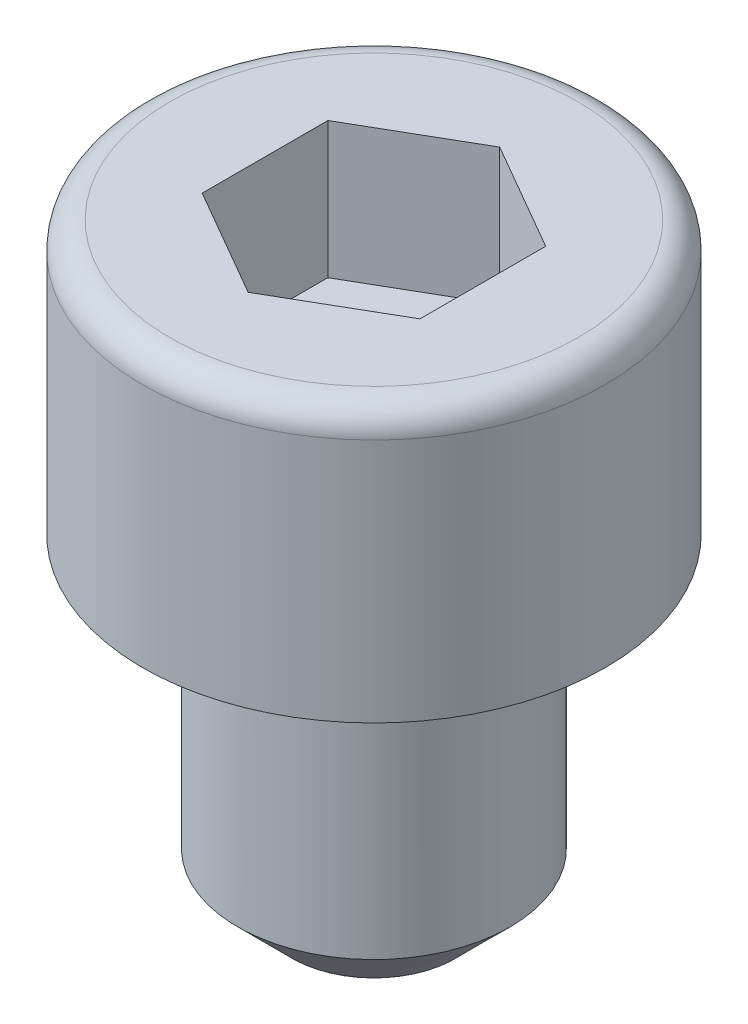
SolidWorks part; units mm, degrees
material "1.4301 (X5CrNi18-10)"
ref_plane "Front Plane" through (0, 0, 0) normal (0, 0, 1) x (1, 0, 0)
ref_plane "Top Plane" through (0, 0, 0) normal (0, 1, 0) x (1, 0, 0)
ref_plane "Right Plane" through (0, 0, 0) normal (1, 0, 0) x (0, 0, -1)
sketch "Sketch1" plane through (0, 0, 0) normal (0, 0, 1) x (1, 0, 0)
  line L0 (0, -1000) -> (0, 49000) construction
  line L1 (0, 0) -> (0, 11)
  line L2 (0, 11) -> (-4.25, 11)
  line L3 (-4.25, 11) -> (-4.25, 6)
  line L4 (-4.25, 6) -> (-2.5, 6)
  line L5 (-2.5, 6) -> (-2.5, 0)
  line L6 (-2.5, 0) -> (0, 0)
  dimension "Imenski premer" = 5
  dimension "Dolzina stebla" = 6
  dimension "Visina glave" = 5
  dimension "Premer glave" = 8.5
revolve "Revolve1" add sketch "Sketch1" angle 360 about L0
sketch "Sketch2" plane through (0, 11, 0) normal (0, 1, 0) x (1, 0, 0)
  line L1 (0, 2.3094) -> (-2, 1.1547)
  line L2 (-2, 1.1547) -> (-2, -1.1547)
  line L3 (-2, -1.1547) -> (0, -2.3094)
  line L4 (0, -2.3094) -> (2, -1.1547)
  line L5 (2, -1.1547) -> (2, 1.1547)
  line L6 (2, 1.1547) -> (0, 2.3094)
  circle A0 centre (0, 0) radius 2 construction
  dimension "Dimenzija kljuca" = 4
extrude "Cut-Extrude1" cut sketch "Sketch2" against normal blind 2.5
fillet "Fillet1" radius 0.5 1 edges at (4.25, 11, 0)
chamfer "Chamfer1" distance 1 angle 45 1 edges at (2.5, 0, 0)
